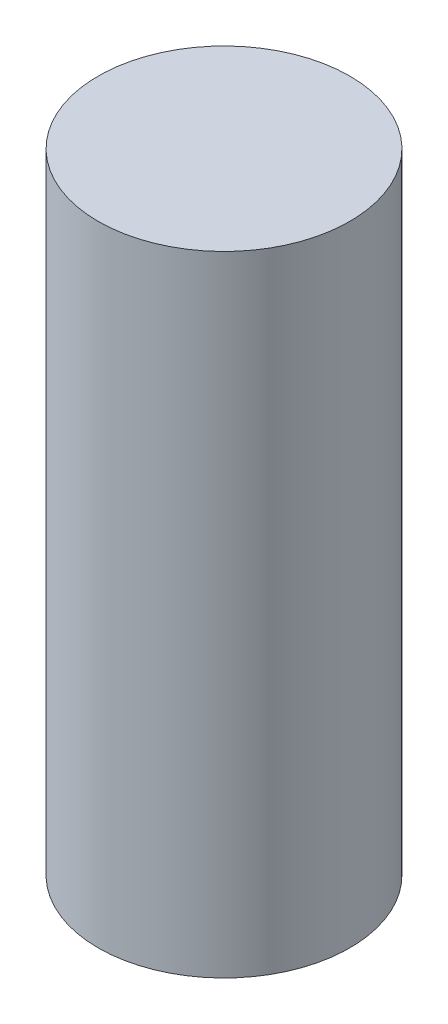
SolidWorks part; units mm, degrees
ref_plane "Front Plane" through (0, 0, 0) normal (0, 0, 1) x (1, 0, 0)
ref_plane "Top Plane" through (0, 0, 0) normal (0, 1, 0) x (1, 0, 0)
ref_plane "Right Plane" through (0, 0, 0) normal (1, 0, 0) x (0, 0, -1)
other "Configuration Table"
sketch "草图1" plane through (0, 0, 0) normal (0, 1, 0) x (1, 0, 0)
  circle A0 centre (0, 0) radius 2
  dimension "D1" = 4
extrude "凸台-拉伸1" add sketch "草图1" along normal blind 10
